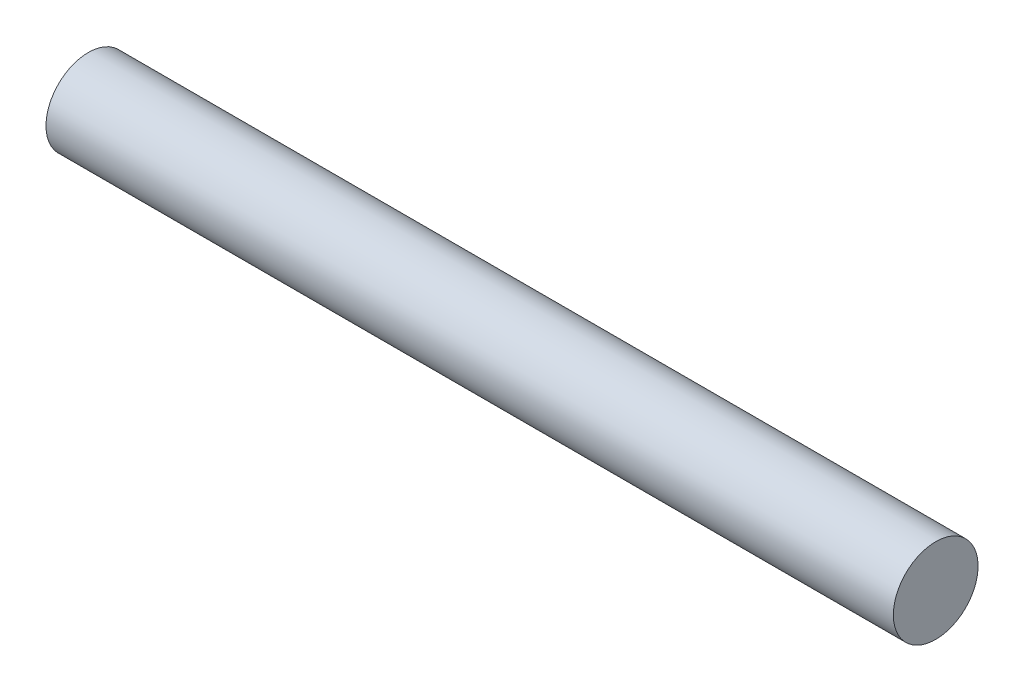
SolidWorks part; units mm, degrees
ref_plane "Front Plane" through (0, 0, 0) normal (0, 0, 1) x (1, 0, 0)
ref_plane "Top Plane" through (0, 0, 0) normal (0, 1, 0) x (1, 0, 0)
ref_plane "Right Plane" through (0, 0, 0) normal (1, 0, 0) x (0, 0, -1)
sketch "Sketch1" plane through (0, 0, 0) normal (1, 0, 0) x (0, 0, -1)
  circle A0 centre (0, 0) radius 0.5
  dimension "D1" = 1
extrude "Boss-Extrude1" add sketch "Sketch1" along normal blind 10
